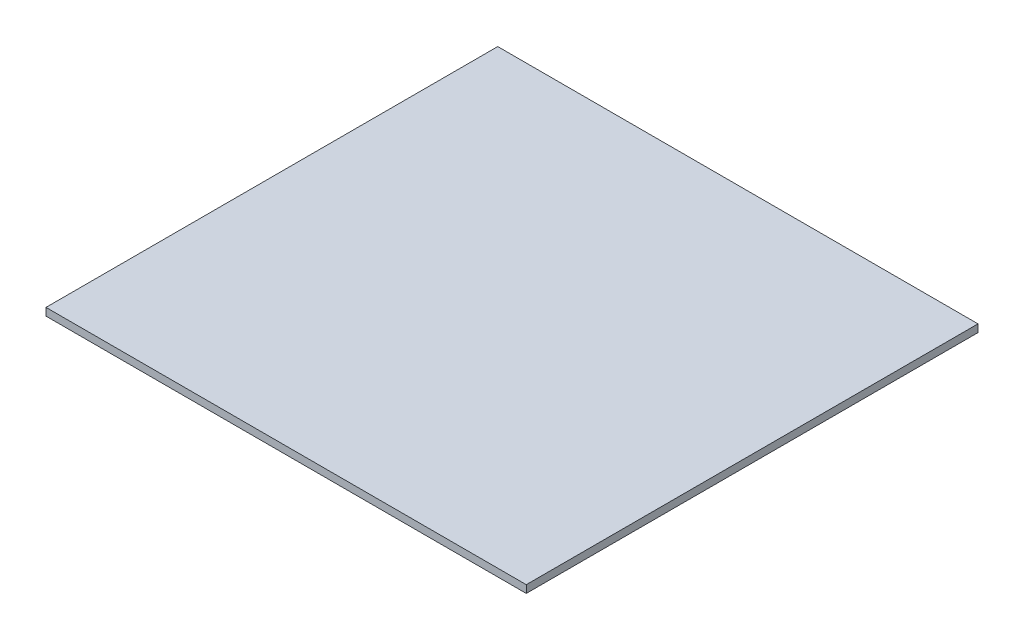
SolidWorks part; units mm, degrees
ref_plane "Front Plane" through (0, 0, 0) normal (0, 0, 1) x (1, 0, 0)
ref_plane "Top Plane" through (0, 0, 0) normal (0, 1, 0) x (1, 0, 0)
ref_plane "Right Plane" through (0, 0, 0) normal (1, 0, 0) x (0, 0, -1)
sketch "Sketch1" plane through (0, 0, 0) normal (0, 0, 1) x (1, 0, 0)
  line L1 (101, -1.6) -> (-101, -1.6)
  line L2 (101, -1.6) -> (101, 1.6)
  line L3 (101, 1.6) -> (-101, 1.6)
  line L4 (-101, -1.6) -> (-101, 1.6)
  line L5 (101, -1.6) -> (-101, 1.6) construction
  line L6 (101, 1.6) -> (-101, -1.6) construction
  point P1 (0, 0)
  dimension "D1" = 3.2
  dimension "D2" = 202
extrude "Boss-Extrude1" add sketch "Sketch1" along normal blind 190
